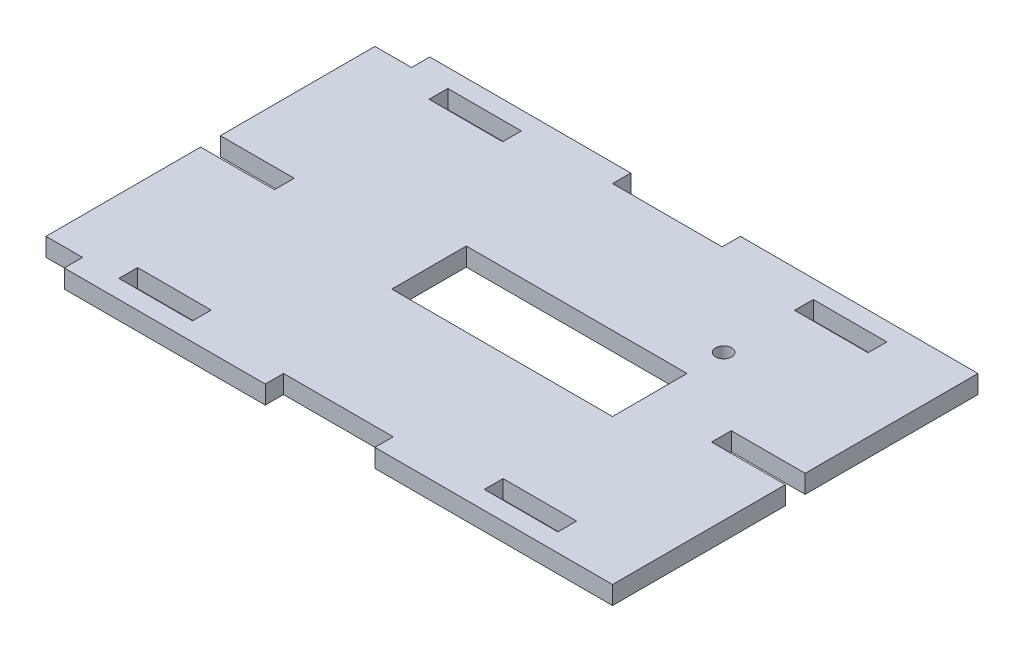
SolidWorks part; units mm, degrees
ref_plane "Front Plane" through (0, 0, 0) normal (0, 0, 1) x (1, 0, 0)
ref_plane "Top Plane" through (0, 0, 0) normal (0, 1, 0) x (1, 0, 0)
ref_plane "Right Plane" through (0, 0, 0) normal (1, 0, 0) x (0, 0, -1)
sketch "Sketch1" plane through (0, 0, 0) normal (0, 1, 0) x (1, 0, 0)
  line L0 (0, 63.5) -> (203.2, 63.5) construction
  line L1 (0, 0) -> (203.2, 0)
  line L2 (0, 0) -> (0, 60.071)
  line L3 (0, 127) -> (203.2, 127)
  line L4 (203.2, 0) -> (203.2, 60.071)
  line L5 (152.4, 76.2) -> (76.2, 76.2) construction
  line L6 (152.4, 76.2) -> (152.4, 50.8) construction
  line L7 (152.4, 50.8) -> (76.2, 50.8) construction
  line L8 (76.2, 76.2) -> (76.2, 50.8) construction
  line L9 (152.654, 76.454) -> (75.946, 76.454)
  line L10 (75.946, 76.454) -> (75.946, 50.546)
  line L11 (152.654, 50.546) -> (75.946, 50.546)
  line L12 (152.654, 76.454) -> (152.654, 50.546)
  line L13 (0, 66.929) -> (25.654, 66.929)
  line L14 (0, 66.675) -> (25.4, 66.675) construction
  line L16 (0, 60.325) -> (25.4, 60.325) construction
  line L17 (25.4, 66.675) -> (25.4, 60.325) construction
  line L18 (177.8, 66.675) -> (203.2, 66.675) construction
  line L19 (177.8, 66.675) -> (177.8, 60.325) construction
  line L20 (177.8, 60.325) -> (203.2, 60.325) construction
  line L22 (25.654, 66.929) -> (25.654, 60.071)
  line L23 (0, 60.071) -> (25.654, 60.071)
  line L24 (177.546, 66.929) -> (203.2, 66.929)
  line L25 (177.546, 66.929) -> (177.546, 60.071)
  line L26 (177.546, 60.071) -> (203.2, 60.071)
  line L27 (0, 66.929) -> (0, 127)
  line L28 (203.2, 66.929) -> (203.2, 127)
  circle A0 centre (152.654, 89.154) radius 2.7781
  dimension "D7" = 5.5562
  dimension "D1" = 203.2
  dimension "D2" = 127
  dimension "D3" = 127
  dimension "D4" = 25.4
  dimension "D5" = 76.2
  dimension "D8" = 12.7
  dimension "D9" = 25.4
  dimension "D10" = 6.35
  dimension "D6" = 0.254
  dimension "D11" = 0.254
  dimension "D12" = 0.254
extrude "Boss-Extrude1" add sketch "Sketch1" along normal blind 6.35
sketch "Sketch4" plane through (0, 6.35, 0) normal (0, 1, 0) x (1, 0, 0)
  line L0 (0, 0) -> (203.2, 0) construction
  line L1 (25.4, 6.4262) -> (50.8, 6.4262) construction
  line L2 (25.4, 6.4262) -> (25.4, 12.7762) construction
  line L3 (25.4, 12.7762) -> (50.8, 12.7762) construction
  line L4 (50.8, 6.4262) -> (50.8, 12.7762) construction
  line L5 (0, 60.071) -> (0, 0) construction
  line L6 (101.6, 0) -> (101.6, 127) construction
  line L7 (203.2, 127) -> (0, 127) construction
  line L8 (0, 63.5) -> (196.85, 63.5) construction
  line L9 (0, 66.929) -> (0, 60.071)
  line L10 (0, 127) -> (0, 66.929) construction
  line L11 (0, 66.929) -> (25.654, 66.929) construction
  line L12 (25.654, 60.071) -> (0, 60.071) construction
  line L13 (203.2, 60.071) -> (203.2, 66.929)
  line L14 (203.2, 60.071) -> (177.546, 60.071) construction
  line L15 (203.2, 0) -> (203.2, 60.071) construction
  line L16 (152.4, 6.4262) -> (152.4, 12.7762) construction
  line L17 (177.8, 12.7762) -> (152.4, 12.7762) construction
  line L18 (177.8, 6.4262) -> (177.8, 12.7762) construction
  line L19 (177.8, 6.4262) -> (152.4, 6.4262) construction
  line L20 (177.8, 120.5738) -> (152.4, 120.5738) construction
  line L21 (177.8, 120.5738) -> (177.8, 114.2238) construction
  line L22 (177.8, 114.2238) -> (152.4, 114.2238) construction
  line L23 (152.4, 120.5738) -> (152.4, 114.2238) construction
  line L24 (50.8, 120.5738) -> (50.8, 114.2238) construction
  line L25 (25.4, 114.2238) -> (50.8, 114.2238) construction
  line L26 (25.4, 120.5738) -> (25.4, 114.2238) construction
  line L27 (25.4, 120.5738) -> (50.8, 120.5738) construction
  line L28 (50.8762, 120.65) -> (50.8762, 114.1476)
  line L29 (25.3238, 114.1476) -> (50.8762, 114.1476)
  line L30 (25.3238, 120.65) -> (25.3238, 114.1476)
  line L31 (25.3238, 120.65) -> (50.8762, 120.65)
  line L32 (177.8762, 120.65) -> (152.3238, 120.65)
  line L33 (152.3238, 120.65) -> (152.3238, 114.1476)
  line L34 (177.8762, 114.1476) -> (152.3238, 114.1476)
  line L35 (177.8762, 120.65) -> (177.8762, 114.1476)
  line L36 (25.3238, 6.35) -> (50.8762, 6.35)
  line L37 (50.8762, 6.35) -> (50.8762, 12.8524)
  line L38 (25.3238, 12.8524) -> (50.8762, 12.8524)
  line L39 (25.3238, 6.35) -> (25.3238, 12.8524)
  line L40 (152.3238, 6.35) -> (152.3238, 12.8524)
  line L41 (177.8762, 12.8524) -> (152.3238, 12.8524)
  line L42 (177.8762, 6.35) -> (177.8762, 12.8524)
  line L43 (177.8762, 6.35) -> (152.3238, 6.35)
  line L44 (12.7, 127) -> (12.7, 120.65)
  line L45 (0, 0) -> (12.7, 0)
  line L46 (0, 0) -> (0, 6.35)
  line L47 (0, 6.35) -> (12.7, 6.35)
  line L48 (12.7, 0) -> (12.7, 6.35)
  line L49 (82.55, 0) -> (120.65, 0)
  line L50 (82.55, 0) -> (82.55, 6.35)
  line L51 (82.55, 6.35) -> (120.65, 6.35)
  line L52 (120.65, 0) -> (120.65, 6.35)
  line L53 (0, 120.65) -> (12.7, 120.65)
  line L54 (0, 127) -> (0, 120.65)
  line L55 (0, 127) -> (12.7, 127)
  line L56 (120.65, 127) -> (120.65, 120.65)
  line L57 (82.55, 120.65) -> (120.65, 120.65)
  line L58 (82.55, 127) -> (82.55, 120.65)
  line L59 (82.55, 127) -> (120.65, 127)
  line M8 (0, 60.071) -> (0, 0)
  line M9 (0, 0) -> (203.2, 0)
  line M15 (203.2, 127) -> (0, 127)
  line M16 (0, 127) -> (0, 66.929)
  dimension "D1" = 25.4
  dimension "D2" = 25.4
  dimension "D3" = 6.35
  dimension "D8" = 6.35
  dimension "D9" = 12.7
  dimension "D10" = 6.35
  dimension "D11" = 6.35
  dimension "D12" = 38.1
  dimension "D4" = 0.0762
  dimension "D5" = 0.0762
  dimension "D6" = 0.0762
  dimension "D7" = 0.0762
extrude "Cut-Extrude1" cut sketch "Sketch4" against normal through all contours L53 L44 M16 M15 | L31 L30 L29 L28 | L58 L57 L56 M15 | L35 L32 L33 L34 | L43 L42 L41 L40 | L52 L51 L50 M9 | L39 L36 L37 L38 | L48 L47 M9 M8
